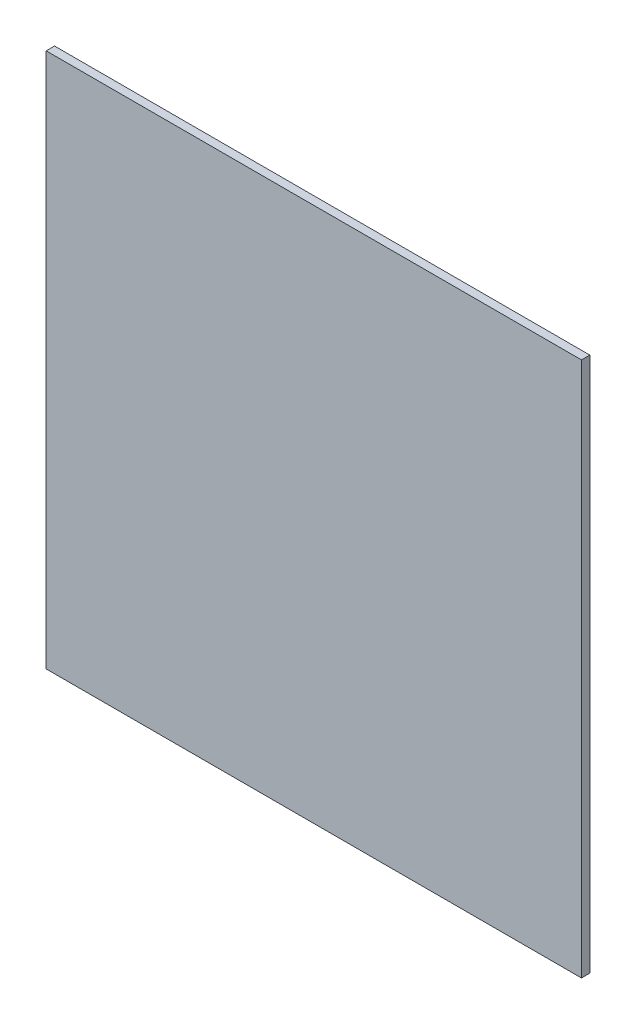
SolidWorks part; units mm, degrees
ref_plane "Front Plane" through (0, 0, 0) normal (0, 0, 1) x (1, 0, 0)
ref_plane "Top Plane" through (0, 0, 0) normal (0, 1, 0) x (1, 0, 0)
ref_plane "Right Plane" through (0, 0, 0) normal (1, 0, 0) x (0, 0, -1)
sketch "Sketch1" plane through (0, 0, 0) normal (0, 0, 1) x (1, 0, 0)
  line L0 (-199.8082, 548.9684) -> (-182.4335, 501.232)
  line L1 (-182.4335, -501.232) -> (-199.8082, -548.9684)
  line L2 (-199.8082, 548.9684) -> (0, 0) construction
  line L3 (0, 0) -> (-199.8082, -548.9684) construction
  line L4 (0, 0) -> (-584.2, 0) construction
  line L5 (-47.4082, 548.9684) -> (-30.0335, 501.232)
  line L8 (-30.0335, -501.232) -> (-47.4082, -548.9684)
  line L9 (104.9918, 548.9684) -> (122.3665, 501.232)
  line L10 (122.3665, -501.232) -> (104.9918, -548.9684)
  line L11 (257.3918, 548.9684) -> (274.7665, 501.232)
  line L14 (274.7665, -501.232) -> (257.3918, -548.9684)
  line L15 (409.7918, 548.9684) -> (427.1665, 501.232)
  line L16 (427.1665, -501.232) -> (409.7918, -548.9684)
  line L17 (562.1918, 548.9684) -> (579.5665, 501.232)
  line L18 (579.5665, -501.232) -> (562.1918, -548.9684)
  arc A0 (-199.8082, 548.9684) -> (-199.8082, -548.9684) centre (0, 0) ccw
  arc A1 (-182.4335, 501.232) -> (-182.4335, -501.232) centre (0, 0) ccw
  arc A6 (-30.0335, 501.232) -> (-30.0335, -501.232) centre (152.4, 0) ccw
  arc A7 (-47.4082, 548.9684) -> (-47.4082, -548.9684) centre (152.4, 0) ccw
  arc A8 (122.3665, 501.232) -> (122.3665, -501.232) centre (304.8, 0) ccw
  arc A9 (104.9918, 548.9684) -> (104.9918, -548.9684) centre (304.8, 0) ccw
  arc A10 (274.7665, 501.232) -> (274.7665, -501.232) centre (457.2, 0) ccw
  arc A11 (257.3918, 548.9684) -> (257.3918, -548.9684) centre (457.2, 0) ccw
  arc A12 (427.1665, 501.232) -> (427.1665, -501.232) centre (609.6, 0) ccw
  arc A13 (409.7918, 548.9684) -> (409.7918, -548.9684) centre (609.6, 0) ccw
  arc A14 (579.5665, 501.232) -> (579.5665, -501.232) centre (762, 0) ccw
  arc A15 (562.1918, 548.9684) -> (562.1918, -548.9684) centre (762, 0) ccw
  dimension "D2" = 584.2
  dimension "D3" = 533.4
  dimension "D1" = 70
  dimension "D4" = 6
  dimension "D5" = 457.2
extrude "Boss-Extrude1" add sketch "Sketch1" along normal blind 19.05
sketch "Sketch2" plane through (0, 0, 19.05) normal (0, 0, 1) x (1, 0, 0)
  line L2 (609.6, 609.6) -> (-609.6, 609.6)
  line L3 (609.6, 609.6) -> (609.6, -609.6)
  line L4 (609.6, -609.6) -> (-609.6, -609.6)
  line L5 (-609.6, 609.6) -> (-609.6, -609.6)
  line L6 (609.6, 609.6) -> (-609.6, -609.6) construction
  line L7 (609.6, -609.6) -> (-609.6, 609.6) construction
  point P0 (0, 0)
  dimension "D2" = 1219.2
  dimension "D3" = 1219.2
extrude "Stock" add sketch "Sketch2" against normal blind 19.05 separate body
sketch "Sketch3" plane through (0, 0, 19.05) normal (0, 0, 1) x (1, 0, 0)
  line L0 (609.6, 0) -> (482.6, 0) construction
  line L1 (609.6, -609.6) -> (609.6, 609.6) construction
  point P4 (0, 0)
  point P5 (609.6, 0)
  dimension "D1" = 127
